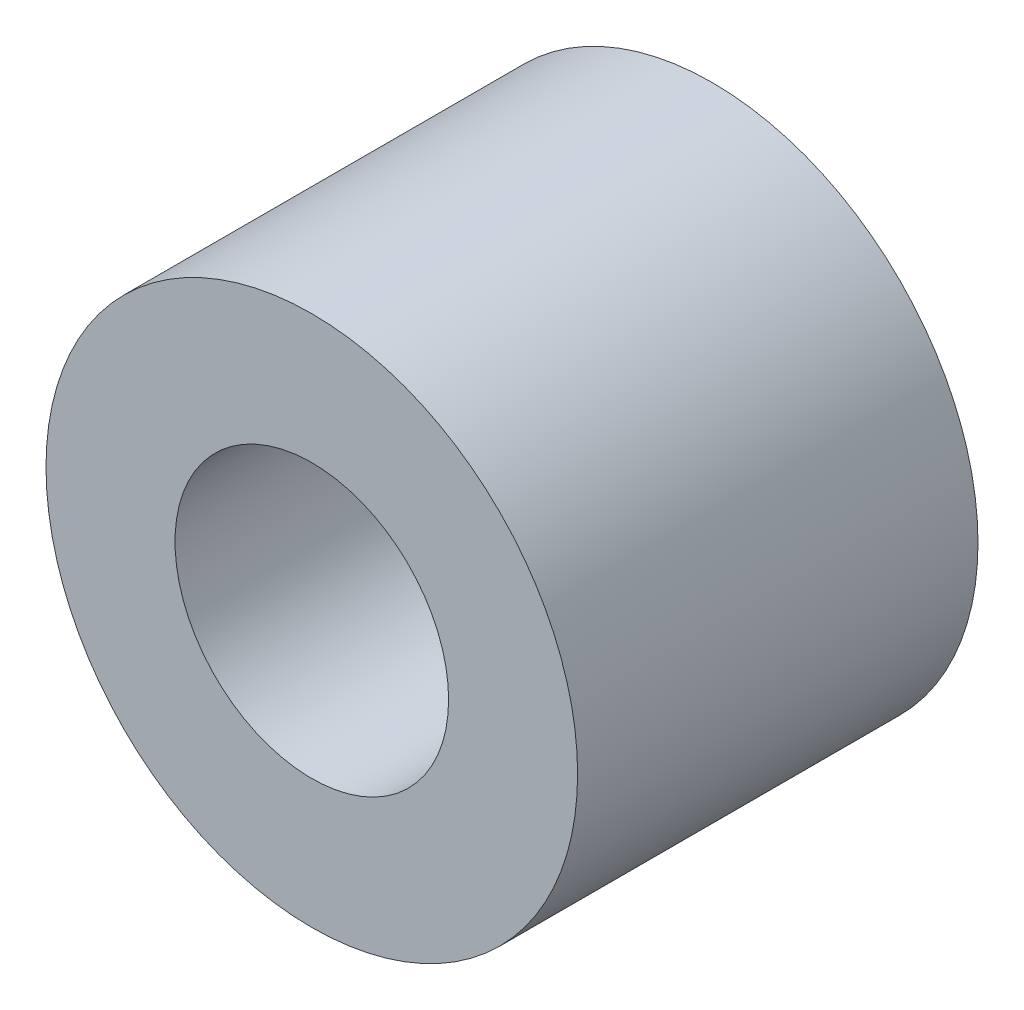
SolidWorks part; units mm, degrees
ref_plane "Front Plane" through (0, 0, 0) normal (0, 0, 1) x (1, 0, 0)
ref_plane "Top Plane" through (0, 0, 0) normal (0, 1, 0) x (1, 0, 0)
ref_plane "Right Plane" through (0, 0, 0) normal (1, 0, 0) x (0, 0, -1)
sketch "Sketch1" plane through (0, 0, 0) normal (0, 0, 1) x (1, 0, 0)
  circle A0 centre (0, 0) radius 11.95
  circle A1 centre (0, 0) radius 6.15
  dimension "D1" = 23.9
  dimension "D2" = 12.3
extrude "Boss-Extrude1" add sketch "Sketch1" along normal blind 18
